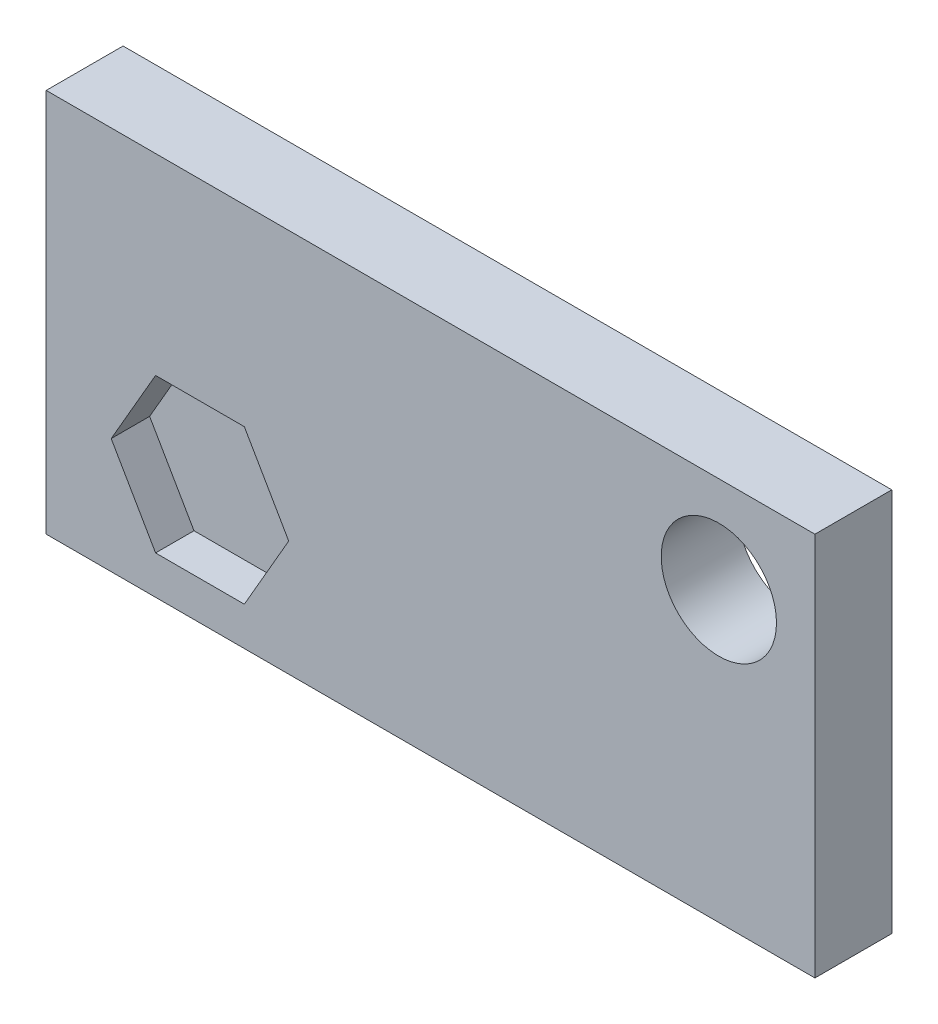
SolidWorks part; units mm, degrees
material "AISI 1020"
ref_plane "Front Plane" through (0, 0, 0) normal (0, 0, 1) x (1, 0, 0)
ref_plane "Top Plane" through (0, 0, 0) normal (0, 1, 0) x (1, 0, 0)
ref_plane "Right Plane" through (0, 0, 0) normal (1, 0, 0) x (0, 0, -1)
sketch "Sketch1" plane through (0, 0, 0) normal (0, 0, 1) x (1, 0, 0)
  line L0 (87.5, 37.5) -> (100, 37.5) construction
  line L1 (0, 0) -> (100, 0)
  line L2 (0, 0) -> (0, 50)
  line L3 (0, 50) -> (100, 50)
  line L4 (100, 0) -> (100, 50)
  line L5 (87.5, 37.5) -> (87.5, 50) construction
  circle A0 centre (87.5, 37.5) radius 7.5
  dimension "D4" = 15
  dimension "D1" = 50
  dimension "D2" = 100
  dimension "D3" = 12.5
extrude "Boss-Extrude1" add sketch "Sketch1" along normal blind 10
sketch "Sketch2" plane through (0, 0, 10) normal (0, 0, 1) x (1, 0, 0)
  line L0 (0, 0) -> (100, 0) construction
  line L1 (25.7735, 25) -> (14.2265, 25)
  line L2 (14.2265, 25) -> (8.453, 15)
  line L3 (8.453, 15) -> (14.2265, 5)
  line L4 (14.2265, 5) -> (25.7735, 5)
  line L5 (25.7735, 5) -> (31.547, 15)
  line L6 (31.547, 15) -> (25.7735, 25)
  line L7 (0, 50) -> (0, 0) construction
  circle A0 centre (20, 15) radius 10 construction
  dimension "D3" = 20
  dimension "D1" = 25
  dimension "D2" = 20
extrude "Cut-Extrude1" cut sketch "Sketch2" against normal blind 5
equation "\"D2@Sketch1\"=\"D1@Sketch1\"*2"
